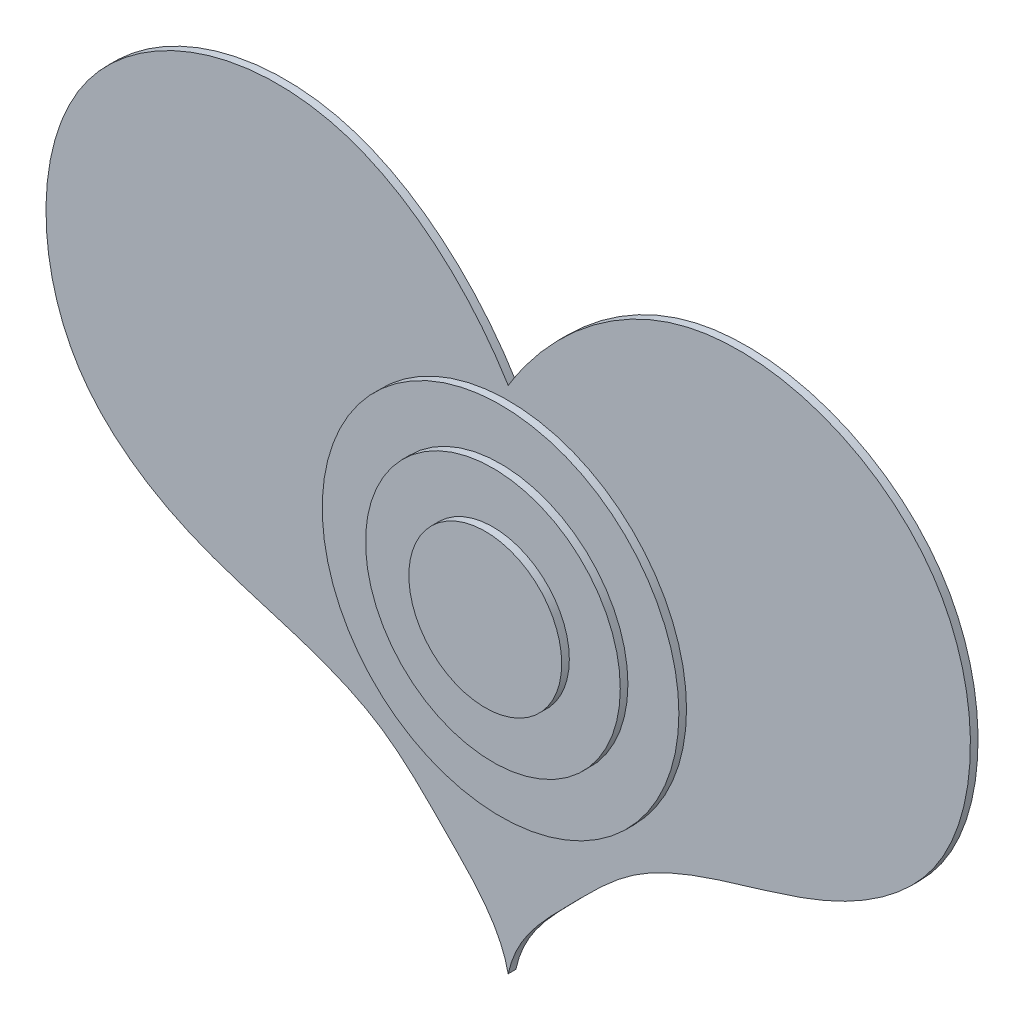
SolidWorks part; units mm, degrees
ref_plane "Front Plane" through (0, 0, 0) normal (0, 0, 1) x (1, 0, 0)
ref_plane "Top Plane" through (0, 0, 0) normal (0, 1, 0) x (1, 0, 0)
ref_plane "Right Plane" through (0, 0, 0) normal (1, 0, 0) x (0, 0, -1)
sketch "Sketch3" plane through (0, 0, 0) normal (0, 0, 1) x (1, 0, 0)
  line L0 (0, 94.186) -> (0, -105.814) construction
  spline S0 degree 3 poles (0, 94.186) (-14.9372, 118.7918) (-53.8376, 154.3852) (-123.7145, 151.3595) (-172.0197, 117.4632) (-186.1231, 62.2376) (-171.6005, 9.5392) (-129.6022, -19.4679) (-86.9144, -30.5957) (-49.1347, -44.2055) (-21.9292, -72.8831) (-3.1414, -91.1314) (0, -105.814) knots 0 0 0 0 0.172688 0.274912 0.387287 0.492001 0.588134 0.688255 0.771841 0.848466 0.917182 1 1 1 1
  spline S1 degree 3 poles (0, 94.186) (14.9372, 118.7918) (53.8376, 154.3852) (123.7145, 151.3595) (172.0197, 117.4632) (186.1231, 62.2376) (171.6005, 9.5392) (129.6022, -19.4679) (86.9144, -30.5957) (49.1347, -44.2055) (21.9292, -72.8831) (3.1414, -91.1314) (0, -105.814) knots 0 0 0 0 0.172688 0.274912 0.387287 0.492001 0.588134 0.688255 0.771841 0.848466 0.917182 1 1 1 1
extrude "Boss-Extrude2" add sketch "Sketch3" against normal blind 3
sketch "Sketch4" plane through (0, 0, 0) normal (0, 0, 1) x (1, 0, 0)
  circle A0 centre (0, 19.1113) radius 70
  dimension "D1" = 140
extrude "Boss-Extrude3" add sketch "Sketch4" along normal blind 3
sketch "Sketch6" plane through (0, 0, 3) normal (0, 0, 1) x (1, 0, 0)
  circle A0 centre (0, 19.1113) radius 50
  dimension "D1" = 100
extrude "Boss-Extrude4" add sketch "Sketch6" along normal blind 3
sketch "Sketch7" plane through (0, 0, 6) normal (0, 0, 1) x (1, 0, 0)
  circle A0 centre (0, 19.1113) radius 30
  dimension "D1" = 60
extrude "Boss-Extrude5" add sketch "Sketch7" along normal blind 3
